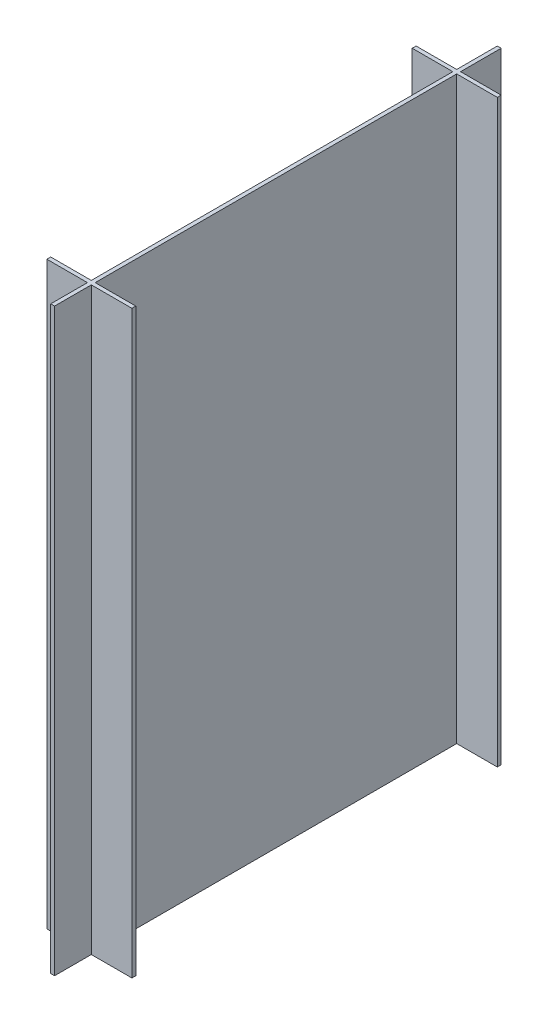
SolidWorks part; units mm, degrees
ref_plane "Front Plane" through (0, 0, 0) normal (0, 0, 1) x (1, 0, 0)
ref_plane "Top Plane" through (0, 0, 0) normal (0, 1, 0) x (1, 0, 0)
ref_plane "Right Plane" through (0, 0, 0) normal (1, 0, 0) x (0, 0, -1)
sketch "Sketch1" plane through (0, 0, 0) normal (0, 1, 0) x (1, 0, 0)
  line L0 (-56.1616, -42.3023) -> (-35.1616, -42.3023)
  line L1 (-33.1616, -42.3023) -> (-12.1616, -42.3023)
  line L2 (-56.1616, -233.3023) -> (-35.1616, -233.3023)
  line L3 (-33.1616, -233.3023) -> (-12.1616, -233.3023)
  line L4 (-35.1616, -42.3023) -> (-35.1616, -21.3023)
  line L5 (-33.1616, -42.3023) -> (-33.1616, -21.3023)
  line L6 (-35.1616, -233.3023) -> (-35.1616, -252.3023)
  line L7 (-33.1616, -233.3023) -> (-33.1616, -252.3023)
  line L8 (-56.1616, -44.3023) -> (-35.1616, -44.3023)
  line L9 (-33.1616, -44.3023) -> (-12.1616, -44.3023)
  line L10 (-33.1616, -44.3023) -> (-33.1616, -231.3023)
  line L11 (-33.1616, -231.3023) -> (-12.1616, -231.3023)
  line L12 (-12.1616, -231.3023) -> (-12.1616, -233.3023)
  line L13 (-56.1616, -42.3023) -> (-56.1616, -44.3023)
  line L14 (-35.1616, -44.3023) -> (-35.1616, -231.3023)
  line L15 (-35.1616, -231.3023) -> (-56.1616, -231.3023)
  line L16 (-56.1616, -231.3023) -> (-56.1616, -233.3023)
  line L17 (-12.1616, -42.3023) -> (-12.1616, -44.3023)
  line L18 (-35.1616, -21.3023) -> (-33.1616, -21.3023)
  line L20 (-35.1616, -252.3023) -> (-33.1616, -252.3023)
  dimension "D1" = 191
  dimension "D2" = 2
  dimension "D3" = 2
  dimension "D4" = 2
  dimension "D5" = 2
  dimension "D6" = 21
  dimension "D7" = 21
  dimension "D8" = 23
  dimension "D9" = 23
extrude "Boss-Extrude1" add sketch "Sketch1" along normal blind 300
